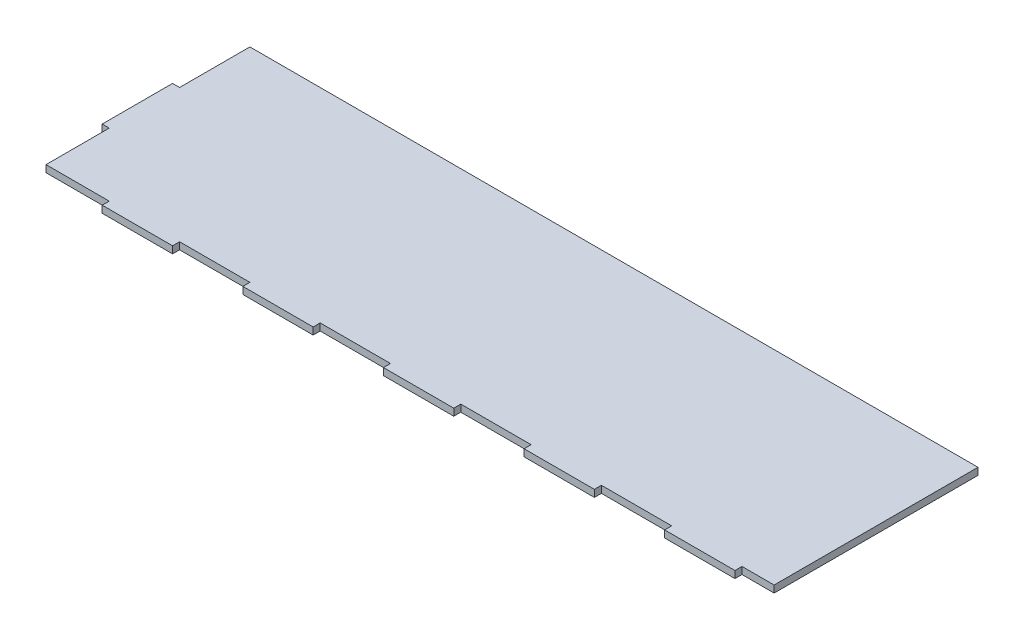
SolidWorks part; units mm, degrees
ref_plane "Front Plane" through (0, 0, 0) normal (0, 0, 1) x (1, 0, 0)
ref_plane "Top Plane" through (0, 0, 0) normal (0, 1, 0) x (1, 0, 0)
ref_plane "Right Plane" through (0, 0, 0) normal (1, 0, 0) x (0, 0, -1)
sketch "Sketch1" plane through (0, 0, 0) normal (0, 1, 0) x (1, 0, 0)
  line L1 (-315, -45) -> (315, -45)
  line L2 (-315, -45) -> (-315, 45)
  line L3 (-315, 45) -> (315, 45)
  line L4 (315, -45) -> (315, 45)
  line L5 (0, 45) -> (0, -45) construction
  line L6 (-315, 0) -> (315, 0) construction
  point P0 (0, 0)
  dimension "D1" = 630
  dimension "D2" = 90
extrude "Boss-Extrude1" add sketch "Sketch1" along normal blind 3
ref_plane "Plane1" through (-255, 0, 0) normal (-1, 0, 0) x (0, 0, 1)
sketch "Sketch3" plane through (0, 3, 0) normal (0, 1, 0) x (1, 0, 0)
  line L0 (-255, 1.65) -> (-255, -1.65) construction
  line L1 (-255, -45) -> (-225, -45)
  line L2 (-255, -45) -> (-255, -42)
  line L3 (-255, -42) -> (-225, -42)
  line L4 (-225, -45) -> (-225, -42)
  line L5 (-315, -45) -> (315, -45) construction
  dimension "D1" = 30
  dimension "D2" = 3
extrude "Cut-Extrude1" cut sketch "Sketch3" against normal blind 3
pattern_linear "LPattern1" count 10 spacing 60 along (1, 0, 0) count 2 spacing 60 along (-1, 0, 0) of "Cut-Extrude1"
ref_plane "Plane2" through (0, 0, -15) normal (0, 0, -1) x (-1, 0, 0)
sketch "Sketch7" plane through (0, 3, 0) normal (0, 1, 0) x (1, 0, 0)
  line L1 (-315, 45) -> (-312, 45)
  line L2 (-315, 45) -> (-315, 15)
  line L3 (-315, 15) -> (-312, 15)
  line L4 (-312, 45) -> (-312, 15)
  dimension "D1" = 30
  dimension "D2" = 3
extrude "Cut-Extrude3" cut sketch "Sketch7" against normal blind 3
ref_plane "Plane3" through (0, 0, 15) normal (0, 0, 1) x (1, 0, 0)
ref_plane "Plane4" through (-312, 3, -45) normal (0, 0, -1) x (-1, 0, 0)
sketch "Sketch13" plane through (0, 3, 0) normal (0, 1, 0) x (1, 0, 0)
  line L0 (-6.6903, -15) -> (6.6903, -15) construction
  line L1 (-315, -42) -> (-312, -42)
  line L2 (-315, -42) -> (-315, -15)
  line L3 (-315, -15) -> (-312, -15)
  line L4 (-312, -42) -> (-312, -15)
  dimension "D1" = 3
extrude "Cut-Extrude4" cut sketch "Sketch13" against normal blind 10
ref_plane "Plane5" through (-1.295, 0, 0) normal (1, 0, 0) x (0, 0, -1)
other "SurfaceCut1"
